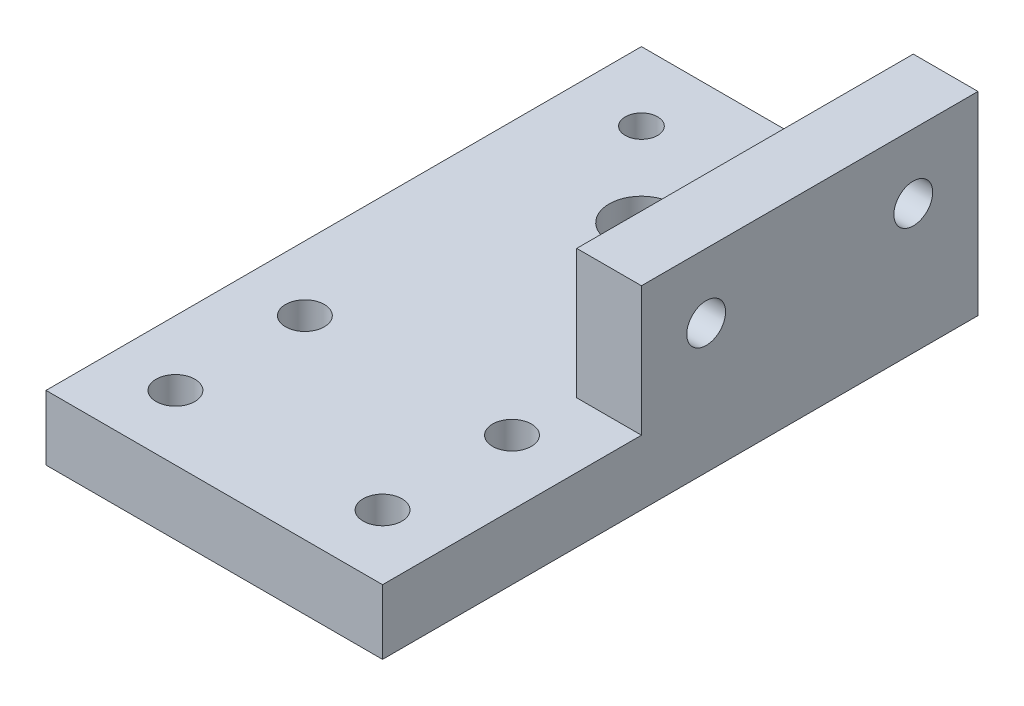
SolidWorks part; units mm, degrees
ref_plane "Front Plane" through (0, 0, 0) normal (0, 0, 1) x (1, 0, 0)
ref_plane "Top Plane" through (0, 0, 0) normal (0, 1, 0) x (1, 0, 0)
ref_plane "Right Plane" through (0, 0, 0) normal (1, 0, 0) x (0, 0, -1)
sketch "Sketch1" plane through (0, 0, 0) normal (0, 1, 0) x (1, 0, 0)
  line L0 (0, 0) -> (52, 0)
  line L1 (52, 0) -> (52, 92)
  line L2 (52, 92) -> (0, 92)
  line L3 (0, 92) -> (0, 0)
  dimension "D1" = 52
  dimension "D2" = 92
extrude "Boss-Extrude1" add sketch "Sketch1" along normal blind 10
sketch "Sketch2" plane through (0, 10, 0) normal (0, 1, 0) x (1, 0, 0)
  line L1 (42, 92) -> (52, 92)
  line L2 (42, 92) -> (42, 40)
  line L3 (42, 40) -> (52, 40)
  line L4 (52, 92) -> (52, 40)
  point P5 (0, 0)
  dimension "D1" = 52
  dimension "D2" = 10
extrude "Boss-Extrude3" add sketch "Sketch2" along normal blind 20
sketch "Sketch5" plane through (0, 10, 0) normal (0, 1, 0) x (1, 0, 0)
  line L0 (0, 92) -> (0, 0) construction
  line L1 (52, 0) -> (52, 40) construction
  line L2 (0, 0) -> (52, 0) construction
  line L3 (42, 92) -> (0, 92) construction
  line L4 (0, 92) -> (40.0494, 51.9506) construction
  circle A0 centre (10, 30) radius 3
  circle A1 centre (42, 30) radius 3
  circle A2 centre (10, 10) radius 3
  circle A3 centre (42, 10) radius 3
  circle A4 centre (23.55, 68.45) radius 5
  circle A5 centre (10.6453, 81.3547) radius 2.5
  circle A6 centre (36.4547, 55.5453) radius 2.5
  point P25 (40.0494, 51.9506)
  dimension "D1" = 6
  dimension "D6" = 10
  dimension "D10" = 5
  dimension "D2" = 10
  dimension "D3" = 10
  dimension "D4" = 10
  dimension "D5" = 20
  dimension "D7" = 23.55
  dimension "D8" = 23.55
  dimension "D9" = 45
  dimension "D11" = 18.25
  dimension "D12" = 18.25
extrude "Cut-Extrude3" cut sketch "Sketch5" against normal up to next
sketch "Sketch6" plane through (42, 0, 0) normal (-1, 0, 0) x (0, 0, 1)
  line L0 (-40, 30) -> (-40, 10) construction
  line L1 (-92, 30) -> (-92, 10) construction
  line L2 (-92, 10) -> (-40, 10) construction
  circle A0 centre (-50, 20.01) radius 3
  circle A1 centre (-82, 20.01) radius 3
  point P4 (0, 0)
  dimension "D4" = 6
  dimension "D1" = 10
  dimension "D2" = 10
  dimension "D3" = 10.01
extrude "Cut-Extrude4" cut sketch "Sketch6" against normal up to next
